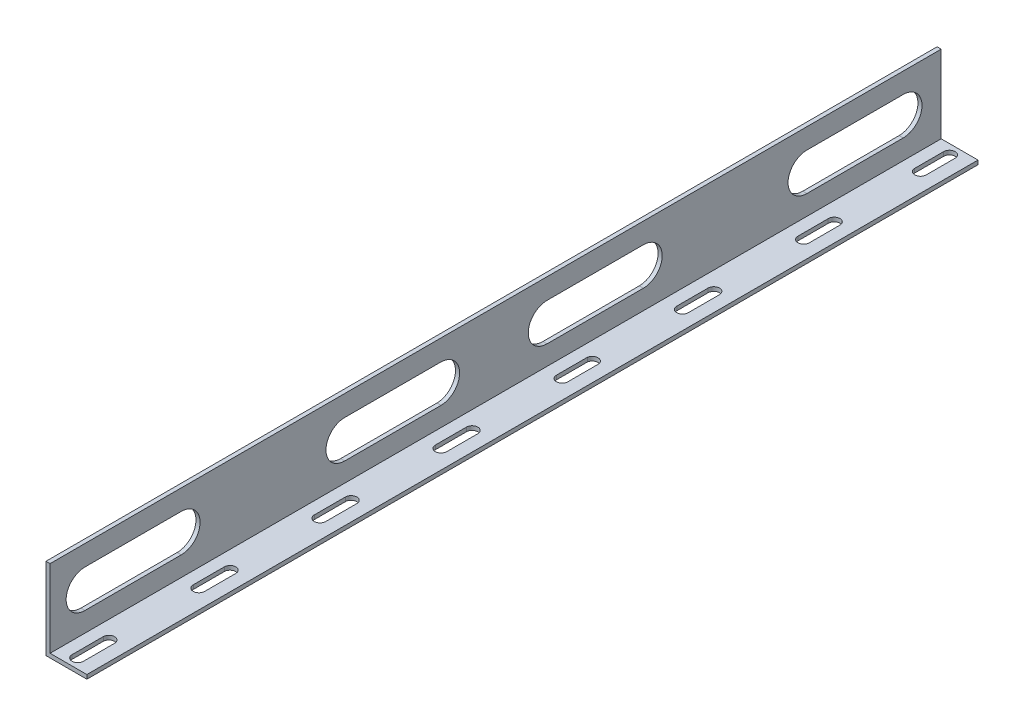
SolidWorks part; units mm, degrees
ref_plane "Front Plane" through (0, 0, 0) normal (0, 0, 1) x (1, 0, 0)
ref_plane "Top Plane" through (0, 0, 0) normal (0, 1, 0) x (1, 0, 0)
ref_plane "Right Plane" through (0, 0, 0) normal (1, 0, 0) x (0, 0, -1)
sketch "Sketch1" plane through (0, 0, 0) normal (0, 0, 1) x (1, 0, 0)
  line L0 (-9.4515, 23.8095) -> (-9.4515, -26.1905)
  line L1 (-9.4515, -26.1905) -> (15.5485, -26.1905)
  line L2 (15.5485, -26.1905) -> (15.5485, -23.6905)
  line L3 (15.5485, -23.6905) -> (-6.9515, -23.6905)
  line L4 (-6.9515, -23.6905) -> (-6.9515, 23.8095)
  line L5 (-6.9515, 23.8095) -> (-9.4515, 23.8095)
  dimension "D1" = 2.5
  dimension "D2" = 2.5
  dimension "D3" = 50
  dimension "D4" = 25
extrude "Boss-Extrude1" add sketch "Sketch1" along normal blind 545
sketch "Sketch2" plane through (-6.9515, 0, 0) normal (1, 0, 0) x (0, 0, -1)
  line L0 (-710.1986, -0.1555) -> (-0.1986, -0.215) construction
  line L6 (-523.6771, 11.3483) -> (-464.779, 11.3483)
  line L7 (-464.779, -11.6631) -> (-523.6771, -11.6631)
  line L9 (-364.779, 11.0878) -> (-305.881, 11.0878)
  line L10 (-305.881, -11.9236) -> (-364.779, -11.9236)
  line L11 (-241.055, 11.2603) -> (-182.157, 11.2603)
  line L12 (-182.157, -11.7511) -> (-241.055, -11.7511)
  line L13 (-82.157, 11.4022) -> (-23.2589, 11.4022)
  line L14 (-23.2589, -11.6092) -> (-82.157, -11.6092)
  arc A25 (-523.6771, -11.6631) -> (-523.6771, 11.3483) centre (-523.6771, -0.1574) cw
  arc A26 (-464.779, 11.3483) -> (-464.779, -11.6631) centre (-464.779, -0.1574) cw
  arc A27 (-364.779, -11.9236) -> (-364.779, 11.0878) centre (-364.779, -0.4179) cw
  arc A28 (-305.881, 11.0878) -> (-305.881, -11.9236) centre (-306.055, -0.4179) cw
  arc A29 (-241.055, -11.7511) -> (-241.055, 11.2603) centre (-241.055, -0.2454) cw
  arc A30 (-182.157, 11.2603) -> (-182.157, -11.7511) centre (-182.157, -0.2454) cw
  arc A31 (-82.157, -11.6092) -> (-82.157, 11.4022) centre (-82.157, -0.1035) cw
  arc A32 (-23.2589, 11.4022) -> (-23.2589, -11.6092) centre (-23.2589, -0.1035) cw
  dimension "D1" = 100
  dimension "D2" = 100
  dimension "D5" = 65
sketch "Sketch3" plane through (0, -23.6905, 0) normal (0, 1, 0) x (1, 0, 0)
  line L0 (4.2985, -700.6581) -> (4.2985, 0) construction
  line L2 (15.5485, 0) -> (-6.9515, 0) construction
  line L8 (0.5708, -242.79) -> (0.5708, -223.79)
  line L9 (7.5708, -242.79) -> (7.5708, -223.79)
  line L12 (0.8077, -169.3528) -> (0.8086, -150.3528)
  line L13 (7.8096, -169.3553) -> (7.8086, -150.3539)
  line L14 (0.5839, -24) -> (0.5839, -6)
  line L15 (7.5839, -24) -> (7.5839, -6)
  line L16 (-9.4515, 0) -> (15.5485, 0) construction
  line L17 (0.5507, -316.8223) -> (0.5507, -297.8223)
  line L18 (7.5507, -316.8223) -> (7.5507, -297.8223)
  line L21 (0.5484, -390.8545) -> (0.5484, -371.8545)
  line L22 (7.5484, -390.8545) -> (7.5484, -371.8545)
  line L25 (0.5439, -464.8868) -> (0.5439, -445.8868)
  line L26 (7.5439, -464.8868) -> (7.5439, -445.8868)
  line L29 (0.482, -538.919) -> (0.482, -519.919)
  line L30 (7.482, -538.919) -> (7.482, -519.919)
  line L35 (15.5485, -545) -> (-6.9515, -545) construction
  line L36 (0.7998, -95.2092) -> (0.7986, -76.8923)
  line L37 (7.8017, -95.2118) -> (7.7987, -76.8907)
  arc A6 (0.5708, -242.79) -> (7.5708, -242.79) centre (4.0708, -242.871) ccw
  arc A7 (0.5708, -223.79) -> (7.5708, -223.79) centre (4.0708, -224.4968) cw
  arc A10 (0.8077, -169.3528) -> (7.8096, -169.3553) centre (4.3086, -169.4968) ccw
  arc A11 (0.8086, -150.3528) -> (7.8086, -150.3539) centre (4.3086, -150.3533) cw
  arc A14 (0.5839, -6) -> (7.5839, -6) centre (4.0839, -6) cw
  arc A15 (0.5839, -24) -> (7.5839, -24) centre (4.0839, -23.7103) ccw
  arc A16 (0.5507, -316.8223) -> (7.5507, -316.8223) centre (4.0507, -316.9033) ccw
  arc A17 (0.5507, -297.8223) -> (7.5507, -297.8223) centre (4.0507, -297.871) cw
  arc A20 (0.5484, -390.8545) -> (7.5484, -390.8545) centre (4.0484, -390.9355) ccw
  arc A21 (0.5484, -371.8545) -> (7.5484, -371.8545) centre (4.0484, -371.9033) cw
  arc A24 (0.5439, -464.8868) -> (7.5439, -464.8868) centre (4.0439, -464.9678) ccw
  arc A25 (0.5439, -445.8868) -> (7.5439, -445.8868) centre (4.0439, -445.9355) cw
  arc A28 (0.482, -538.919) -> (7.482, -538.919) centre (3.982, -539) ccw
  arc A29 (0.482, -519.919) -> (7.482, -519.919) centre (3.982, -519.9678) cw
  arc A30 (0.7998, -95.2092) -> (7.8017, -95.2118) centre (4.3007, -95.3533) ccw
  arc A31 (0.7986, -76.8923) -> (7.7987, -76.8907) centre (4.2986, -76.6971) cw
  point P13 (0, 0)
  point P34 (4.2985, -76.3431)
  point P35 (4.2985, -76.5022)
  dimension "D1" = 7
  dimension "D2" = 18
  dimension "D3" = 18
  dimension "D4" = 55
  dimension "D5" = 55
  dimension "D11" = 6
  dimension "D12" = 6
  dimension "D13" = 55
  dimension "D14" = 55
  dimension "D15" = 55
  dimension "D16" = 55
extrude "Cut-Extrude2" cut sketch "Sketch3" against normal blind 10
extrude "Cut-Extrude3" cut sketch "Sketch2" against normal blind 10
